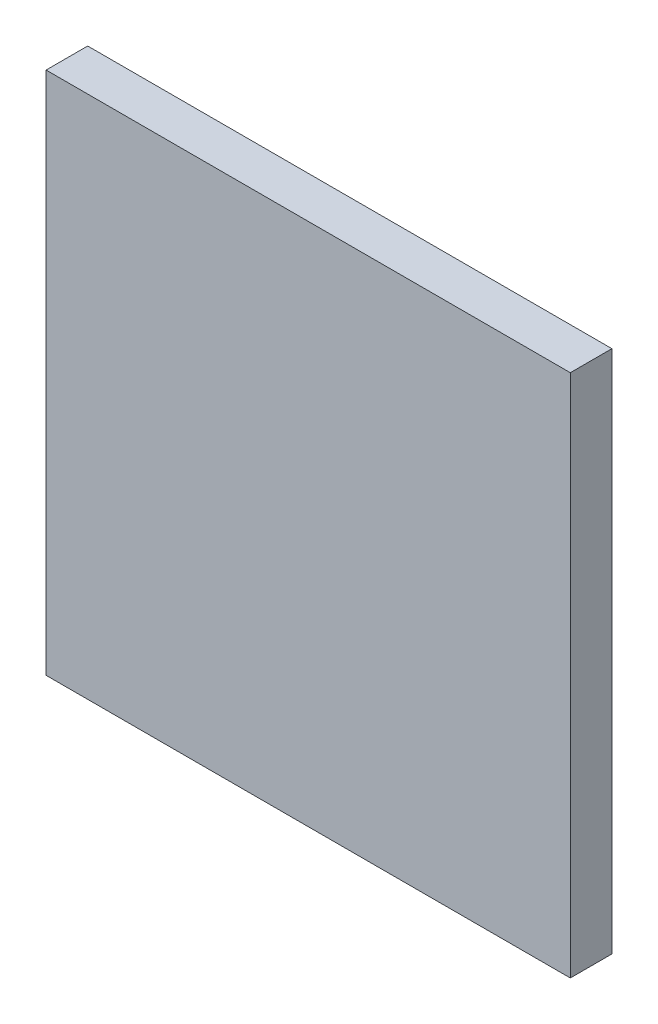
SolidWorks part; units mm, degrees
ref_plane "Ebene vorne" through (0, 0, 0) normal (0, 0, 1) x (1, 0, 0)
ref_plane "Ebene oben" through (0, 0, 0) normal (0, 1, 0) x (1, 0, 0)
ref_plane "Ebene rechts" through (0, 0, 0) normal (1, 0, 0) x (0, 0, -1)
sketch "Skizze1" plane through (0, 0, 0) normal (0, 0, 1) x (1, 0, 0)
  line L0 (-6.2992, 6.2992) -> (6.2992, 6.2992)
  line L1 (6.2992, 6.2992) -> (6.2992, -6.2992)
  line L2 (6.2992, -6.2992) -> (-6.2992, -6.2992)
  line L3 (-6.2992, -6.2992) -> (-6.2992, 6.2992)
extrude "Component_Outline" add sketch "Skizze1" along normal blind 1 separate body
sketch3d "3D-Skizze1"
  line L0 (0, 0, 0) -> (1, 0, 0)
  line L1 (0, 0, 0) -> (0, 1, 0)
  line L2 (0, 0, 0) -> (0, 0, 1)
  point P0 (0, 0, 0)
